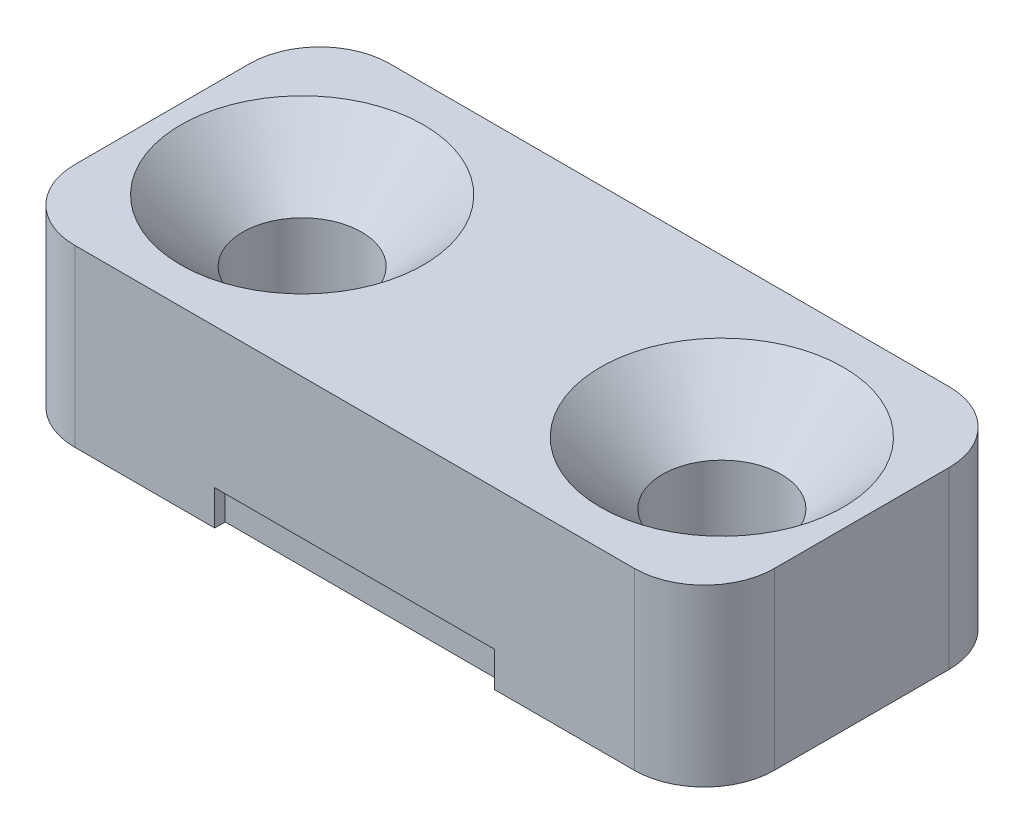
SolidWorks part; units mm, degrees
material "3D printed plastic"
ref_plane "Front Plane" through (0, 0, 0) normal (0, 0, 1) x (1, 0, 0)
ref_plane "Top Plane" through (0, 0, 0) normal (0, 1, 0) x (1, 0, 0)
ref_plane "Right Plane" through (0, 0, 0) normal (1, 0, 0) x (0, 0, -1)
sketch "Sketch1" plane through (0, 0, 0) normal (0, 1, 0) x (1, 0, 0)
  line L0 (-10, 4.5) -> (10, -4.5) construction
  line L1 (-8, 4.5) -> (8, 4.5)
  line L2 (-10, 2.5) -> (-10, -2.5)
  line L3 (-8, -4.5) -> (8, -4.5)
  line L4 (10, 2.5) -> (10, -2.5)
  arc A0 (8, 4.5) -> (10, 2.5) centre (8, 2.5) cw
  arc A1 (-10, -2.5) -> (-8, -4.5) centre (-8, -2.5) ccw
  arc A2 (8, -4.5) -> (10, -2.5) centre (8, -2.5) ccw
  arc A3 (-8, 4.5) -> (-10, 2.5) centre (-8, 2.5) ccw
  point P7 (10, 4.5)
  dimension "D3" = 2
  dimension "D1" = 9
  dimension "D2" = 20
extrude "Boss-Extrude1" add sketch "Sketch1" along normal blind 5
hole_wizard "CSK for M3 Hex Socket Countersunk Head Screw1" positions "Sketch3" profile "Sketch2" countersink size "M3" standard "DIN" end condition through all
sketch "Sketch3" plane through (0, 5, 0) normal (0, 1, 0) x (1, 0, 0)
  line L0 (-6, 0) -> (6, 0) construction
  point P0 (-6, 0)
  point P2 (6, 0)
  dimension "D1" = 12
sketch "Sketch2" plane through (-6, 5, 0) normal (1, 0, 0) x (0, 0, 1)
  line L0 (0, 0) -> (0, 5)
  line L1 (0, 5) -> (1.7, 5)
  line L2 (1.7, 5) -> (1.7, 1.77)
  line L3 (1.7, 1.77) -> (3.47, 0)
  line L5 (3.47, 0) -> (0, 0)
  line L6 (-1.7, 1.77) -> (-3.47, 0) construction
  line L11 (0, -6.35) -> (0, 107.95) construction
  dimension "Thru Hole Dia." = 3.4
  dimension "Thru Hole Depth" = 5
  dimension "Near C'Sink Dia." = 6.94
  dimension "Near C'Sink Angle" = 90
sketch "Sketch5" plane through (0, 0, 0) normal (1, 0, 0) x (0, 0, -1)
  line L0 (1.7, 1) -> (3.3, 1)
  line L1 (-4.5, 0) -> (-2.5, 0) construction
  line L2 (-5.8, 1) -> (-4.2, 1)
  line L3 (-5.8, 1) -> (-5.8, 0)
  line L4 (-5.8, 0) -> (-4.2, 0)
  line L5 (-4.2, 1) -> (-4.2, 0)
  line L6 (-2.5, 0) -> (2.5, 0) construction
  line L7 (-3.3, 1) -> (-1.7, 1)
  line L8 (-3.3, 1) -> (-3.3, 0)
  line L9 (-3.3, 0) -> (-1.7, 0)
  line L10 (-1.7, 1) -> (-1.7, 0)
  line L11 (-0.8, 1) -> (0.8, 1)
  line L12 (-0.8, 1) -> (-0.8, 0)
  line L13 (-0.8, 0) -> (0.8, 0)
  line L14 (0.8, 1) -> (0.8, 0)
  line L15 (1.7, 1) -> (1.7, 0)
  line L16 (1.7, 0) -> (3.3, 0)
  line L17 (3.3, 1) -> (3.3, 0)
  line L19 (2.5, 0) -> (4.5, 0) construction
  line L20 (4.2, 1) -> (5.8, 1)
  line L21 (4.2, 1) -> (4.2, 0)
  line L22 (4.2, 0) -> (5.8, 0)
  line L23 (5.8, 1) -> (5.8, 0)
  dimension "D1" = 1.6
  dimension "D2" = 5
  dimension "D3" = 2.5
  dimension "D4" = 1
extrude "Cut-Extrude1" cut sketch "Sketch5" against normal mid plane 8
